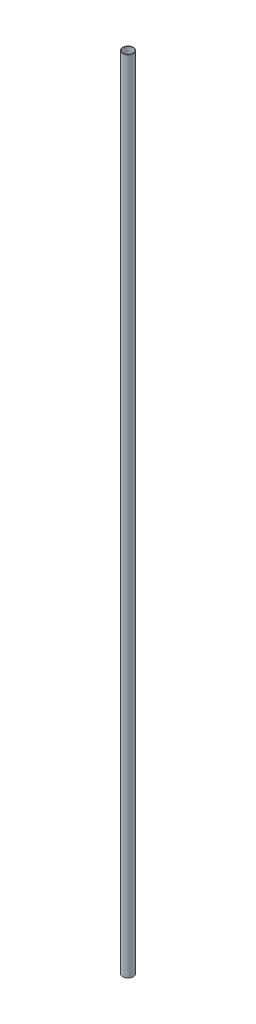
SolidWorks part; units mm, degrees
ref_plane "Front Plane" through (0, 0, 0) normal (0, 0, 1) x (1, 0, 0)
ref_plane "Top Plane" through (0, 0, 0) normal (0, 1, 0) x (1, 0, 0)
ref_plane "Right Plane" through (0, 0, 0) normal (1, 0, 0) x (0, 0, -1)
sketch "Sketch2" plane through (0, 0, 0) normal (0, 1, 0) x (1, 0, 0)
  circle A0 centre (0, 0) radius 6.35
  circle A1 centre (0, 0) radius 6.858
  dimension "D1" = 12.7
  dimension "D2" = 13.716
extrude "Boss-Extrude1" add sketch "Sketch2" along normal blind 1016
